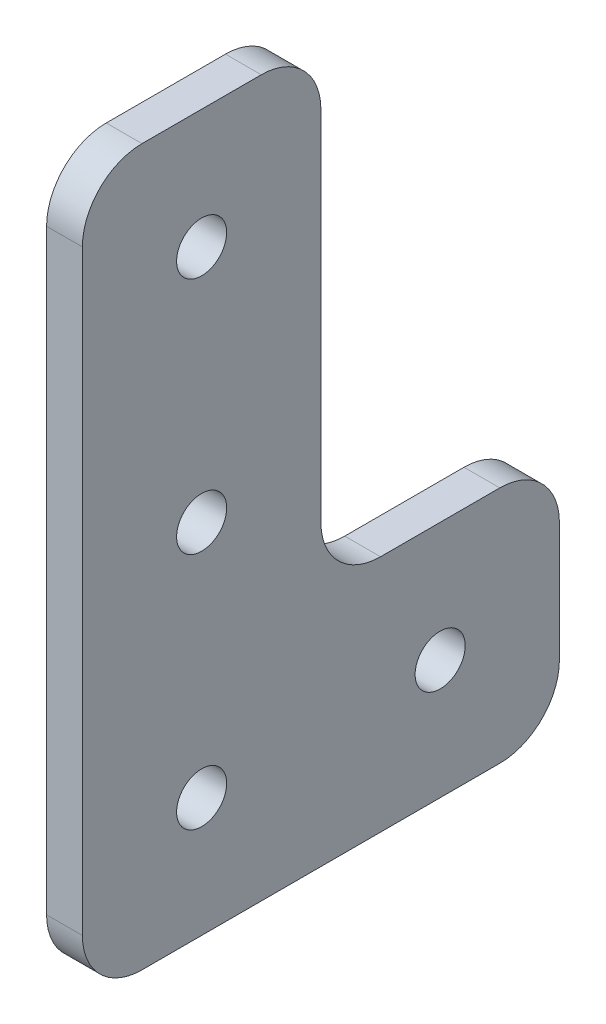
SolidWorks part; units mm, degrees
material "Thornel Mat VMA"
ref_plane "前视基准面" through (0, 0, 0) normal (0, 0, 1) x (1, 0, 0)
ref_plane "上视基准面" through (0, 0, 0) normal (0, 1, 0) x (1, 0, 0)
ref_plane "右视基准面" through (0, 0, 0) normal (1, 0, 0) x (0, 0, -1)
sketch "草图1" plane through (0, 0, 0) normal (1, 0, 0) x (0, 0, -1)
  line L0 (10, -10) -> (30, -10)
  line L1 (-10, 30) -> (10, 30)
  line L2 (-10, 30) -> (-10, -30)
  line L3 (-10, -30) -> (10, -30)
  line L4 (10, 30) -> (10, -10)
  line L5 (-10, 30) -> (10, -30) construction
  line L6 (-10, -30) -> (10, 30) construction
  line L7 (30, -10) -> (30, -30)
  line L8 (30, -30) -> (10, -30)
  circle A0 centre (0, 20) radius 2.1
  circle A1 centre (0, 0) radius 2.1
  circle A2 centre (0, -20) radius 2.1
  circle A3 centre (20, -20) radius 2.1
  point P0 (0, 0)
  dimension "D5" = 4.2
  dimension "D1" = 60
  dimension "D2" = 20
  dimension "D3" = 40
  dimension "D4" = 20
  dimension "D6" = 10
  dimension "D7" = 10
  dimension "D9" = 20
  dimension "D11" = 20
  dimension "D8" = 3
  dimension "D10" = 2
extrude "凸台-拉伸1" add sketch "草图1" along normal blind 3
fillet "圆角2" radius 5 6 edges at (1.5, -30, 10) (1.5, -30, -30) (1.5, -10, -30) (1.5, -10, -10) (1.5, 30, -10) (1.5, 30, 10)
